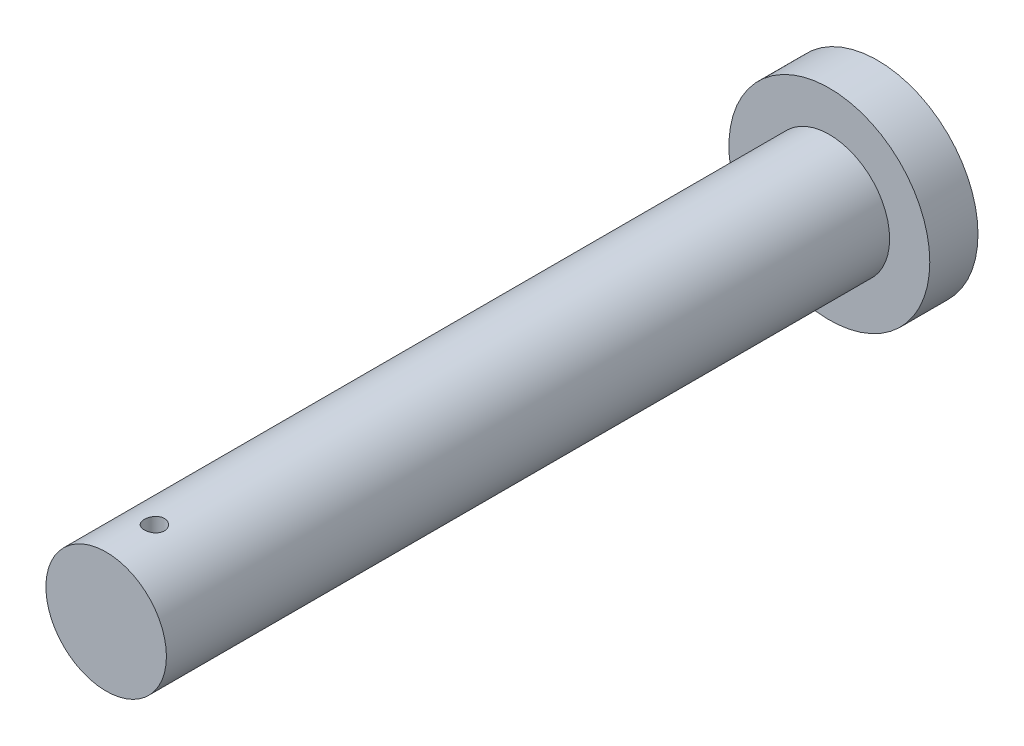
SolidWorks part; units mm, degrees
material "Plain Carbon Steel"
ref_plane "Front Plane" through (0, 0, 0) normal (0, 0, 1) x (1, 0, 0)
ref_plane "Top Plane" through (0, 0, 0) normal (0, 1, 0) x (1, 0, 0)
ref_plane "Right Plane" through (0, 0, 0) normal (1, 0, 0) x (0, 0, -1)
sketch "Sketch1" plane through (0, 0, 0) normal (0, 0, 1) x (1, 0, 0)
  circle A0 centre (0, 0) radius 25
  dimension "D1" = 50
extrude "Boss-Extrude1" add sketch "Sketch1" along normal blind 12
sketch "Sketch2" plane through (0, 0, 12) normal (0, 0, 1) x (1, 0, 0)
  circle A0 centre (0, 0) radius 15
  dimension "D1" = 30
extrude "Boss-Extrude2" add sketch "Sketch2" along normal blind 180
sketch "Sketch3" plane through (0, 0, 0) normal (0, 1, 0) x (1, 0, 0)
  line L0 (-15, -192) -> (15, -192) construction
  circle A0 centre (0, -180) radius 2.5
  point P4 (0, 0)
  dimension "D1" = 5
  dimension "D2" = 12
extrude "Cut-Extrude1" cut sketch "Sketch3" against normal through all both and the other way through all
